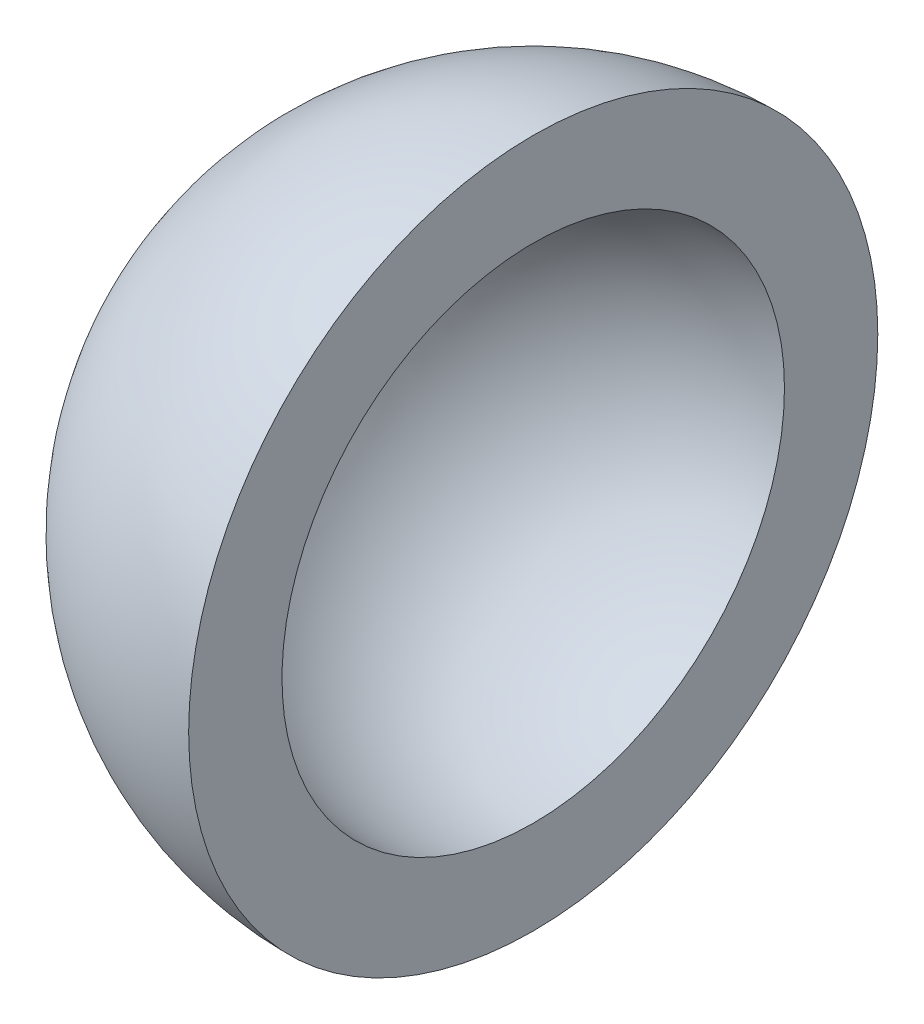
SolidWorks part; units mm, degrees
ref_plane "Front Plane" through (0, 0, 0) normal (0, 0, 1) x (1, 0, 0)
ref_plane "Top Plane" through (0, 0, 0) normal (0, 1, 0) x (1, 0, 0)
ref_plane "Right Plane" through (0, 0, 0) normal (1, 0, 0) x (0, 0, -1)
sketch "Sketch4" plane through (0, 0, 0) normal (0, 0, 1) x (1, 0, 0)
  line L0 (-5.8104, 0) -> (-4.2366, 0)
  line L2 (0, -4.2366) -> (0, -5.8104)
  line L3 (0, -5.0235) -> (0, 0) construction
  line L4 (0, 0) -> (-5.0235, 0) construction
  arc A0 (-5.8104, 0) -> (0, -5.8104) centre (0, 0) ccw
  arc A1 (-4.2366, 0) -> (0, -4.2366) centre (0, 0) ccw
revolve "Revolve3" add sketch "Sketch4" angle 360 about L4
